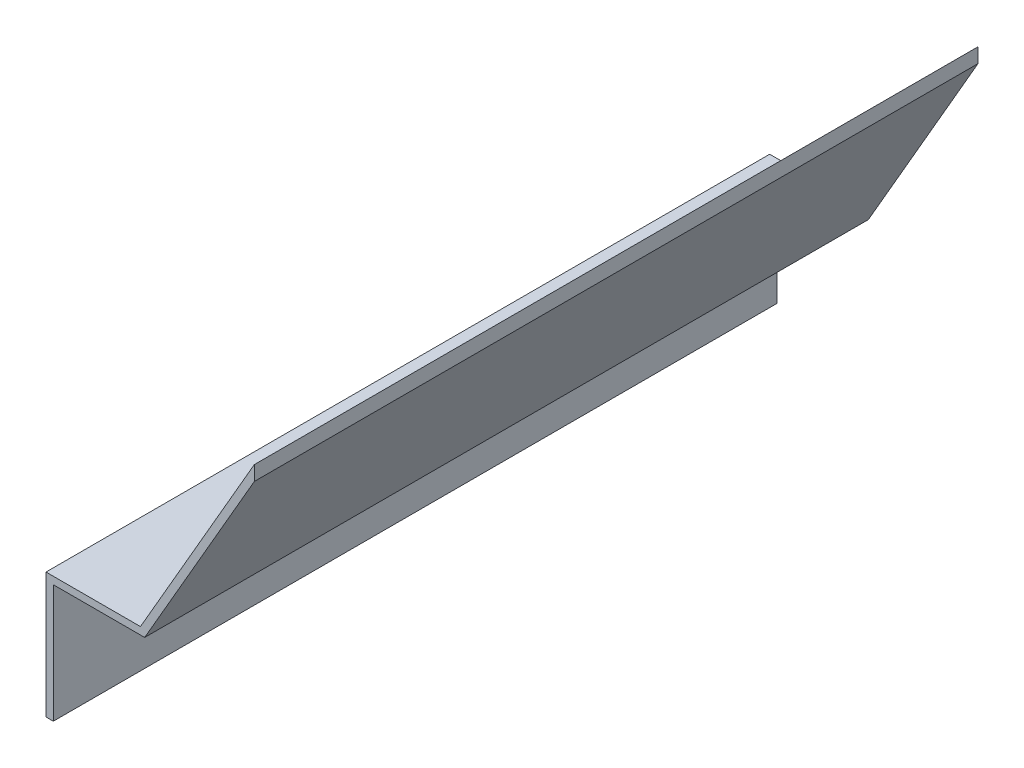
SolidWorks part; units mm, degrees
material "Plain Carbon Steel"
ref_plane "Front Plane" through (0, 0, 0) normal (0, 0, 1) x (1, 0, 0)
ref_plane "Top Plane" through (0, 0, 0) normal (0, 1, 0) x (1, 0, 0)
ref_plane "Right Plane" through (0, 0, 0) normal (1, 0, 0) x (0, 0, -1)
sketch "Sketch1" plane through (0, 0, 0) normal (0, 0, 1) x (1, 0, 0)
  line L0 (-106.8881, 84.1039) -> (-106.8881, 116.4592)
  line L1 (-106.8881, 116.4592) -> (-81.8881, 116.4592)
  line L4 (-81.8881, 116.4592) -> (-51.8881, 168.4207)
  line L5 (-108.8881, 84.1039) -> (-108.8881, 118.4592)
  line L6 (-108.8881, 118.4592) -> (-83.0428, 118.4592)
  line L7 (-83.0428, 118.4592) -> (-53.6202, 169.4207)
  line L8 (-53.6202, 169.4207) -> (-51.8881, 172.4207)
  line L9 (-51.8881, 172.4207) -> (-51.8881, 168.4207)
  line L10 (-108.8881, 84.1039) -> (-106.8881, 84.1039)
  dimension "D2" = 25
  dimension "D1" = 2
extrude "Boss-Extrude1" add sketch "Sketch1" along normal blind 198
